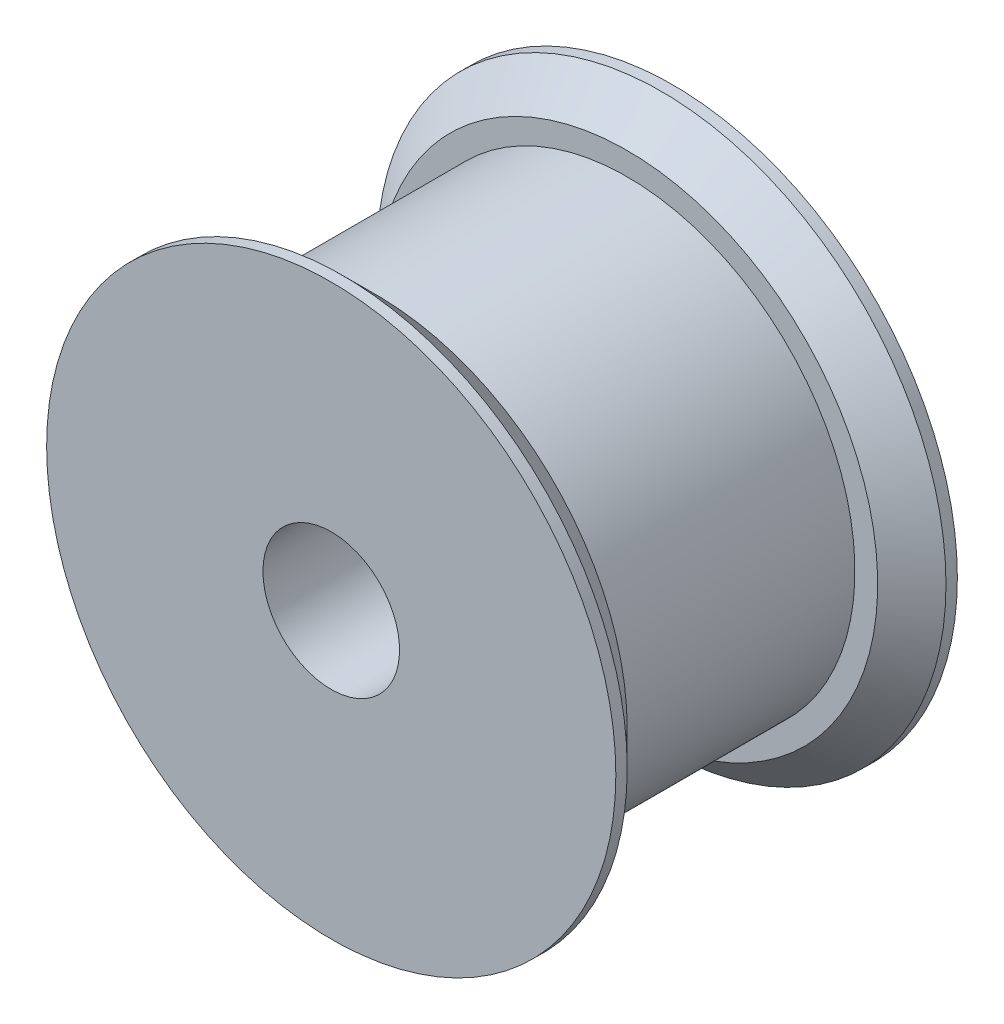
SolidWorks part; units mm, degrees
ref_plane "Front Plane" through (0, 0, 0) normal (0, 0, 1) x (1, 0, 0)
ref_plane "Top Plane" through (0, 0, 0) normal (0, 1, 0) x (1, 0, 0)
ref_plane "Right Plane" through (0, 0, 0) normal (1, 0, 0) x (0, 0, -1)
sketch "Sketch1" plane through (0, 0, 0) normal (0, 1, 0) x (1, 0, 0)
  line L0 (0, 16.7008) -> (0, -15.0615) construction
  line L1 (-15.4713, 0) -> (18.1352, 0) construction
  line L2 (0, 7.5) -> (12.5, 7.5)
  line L3 (12.5, 7.5) -> (12.5, 5.5)
  line L4 (12.5, 5.5) -> (10, 5.5)
  line L5 (10, 5.5) -> (10, -5.5)
  line L6 (12.5, -5.5) -> (10, -5.5)
  line L7 (12.5, -7.5) -> (12.5, -5.5)
  line L8 (0, -7.5) -> (12.5, -7.5)
  line L9 (0, 7.5) -> (0, -7.5)
  point P11 (10, 0)
  dimension "D1" = 12.5
  dimension "D2" = 10
  dimension "D3" = 7.5
  dimension "D4" = 5.5
revolve "Revolve1" add sketch "Sketch1" angle 360 about L0
sketch "Sketch2" plane through (0, 0, -7.5) normal (0, 0, -1) x (-1, 0, 0)
  circle A0 centre (0, 0) radius 3
  dimension "D1" = 6
extrude "Cut-Extrude1" cut sketch "Sketch2" against normal through all
chamfer "Chamfer1" distance 1.5 angle 45 2 edges at (-12.5, 0, -5.5) (-12.5, 0, 5.5)
